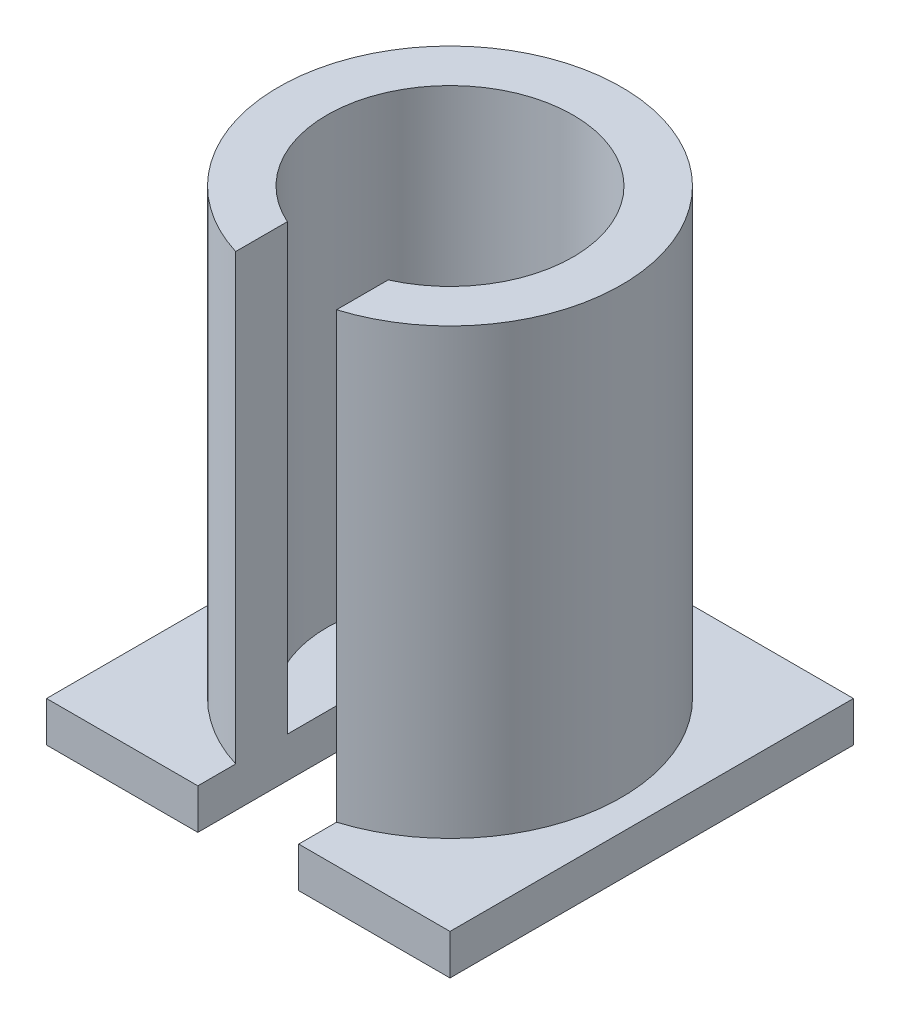
SolidWorks part; units mm, degrees
ref_plane "Front Plane" through (0, 0, 0) normal (0, 0, 1) x (1, 0, 0)
ref_plane "Top Plane" through (0, 0, 0) normal (0, 1, 0) x (1, 0, 0)
ref_plane "Right Plane" through (0, 0, 0) normal (1, 0, 0) x (0, 0, -1)
sketch "Sketch1" plane through (0, 0, 0) normal (0, 1, 0) x (1, 0, 0)
  line L0 (0, 0) -> (0, -4.25)
  circle A0 centre (0, 0) radius 4.25
  circle A1 centre (0, 0) radius 3.05
  dimension "D1" = 8.5
  dimension "D2" = 6.1
extrude "Boss-Extrude1" add sketch "Sketch1" along normal blind 12
sketch "Sketch2" plane through (0, 0, 0) normal (0, 1, 0) x (1, 0, 0)
  circle A0 centre (0, 0) radius 3.05
  circle A1 centre (0, 0) radius 1.25
  dimension "D1" = 6.1
  dimension "D2" = 2.5
extrude "Boss-Extrude2" add sketch "Sketch2" along normal blind 1
sketch "Sketch3" plane through (0, 0, 0) normal (0, 1, 0) x (1, 0, 0)
  line L0 (-1.25, 0) -> (1.25, 0)
  line L1 (-1.25, 0) -> (-1.25, -5.0723)
  line L2 (1.25, 0) -> (1.25, -5.0723)
  line L3 (-1.25, -5.0723) -> (1.25, -5.0723)
  circle A0 centre (0, 0) radius 1.25
extrude "Cut-Extrude1" cut sketch "Sketch3" along normal blind 15 contours A0 L1 L3 L2
sketch "Sketch4" plane through (0, 0, 0) normal (0, 1, 0) x (1, 0, 0)
  line L0 (-1.25, 0) -> (1.25, 0)
  line L1 (5, -5) -> (-5, -5)
  line L2 (5, -5) -> (5, 5)
  line L3 (5, 5) -> (-5, 5)
  line L4 (-5, -5) -> (-5, 5)
  line L5 (5, -5) -> (-5, 5) construction
  line L6 (5, 5) -> (-5, -5) construction
  line L7 (-1.25, 0) -> (-1.25, -6.498)
  line L8 (1.25, 0) -> (1.25, -6.498)
  line L9 (-1.25, -6.498) -> (1.25, -6.498)
  circle A0 centre (0, 0) radius 1.25
  point P0 (0, 0)
  dimension "D3" = 2.5
  dimension "D1" = 10
  dimension "D2" = 10
extrude "Boss-Extrude3" add sketch "Sketch4" along normal blind 1 contours A0 L8 L1 L2 L3 L4 L7
